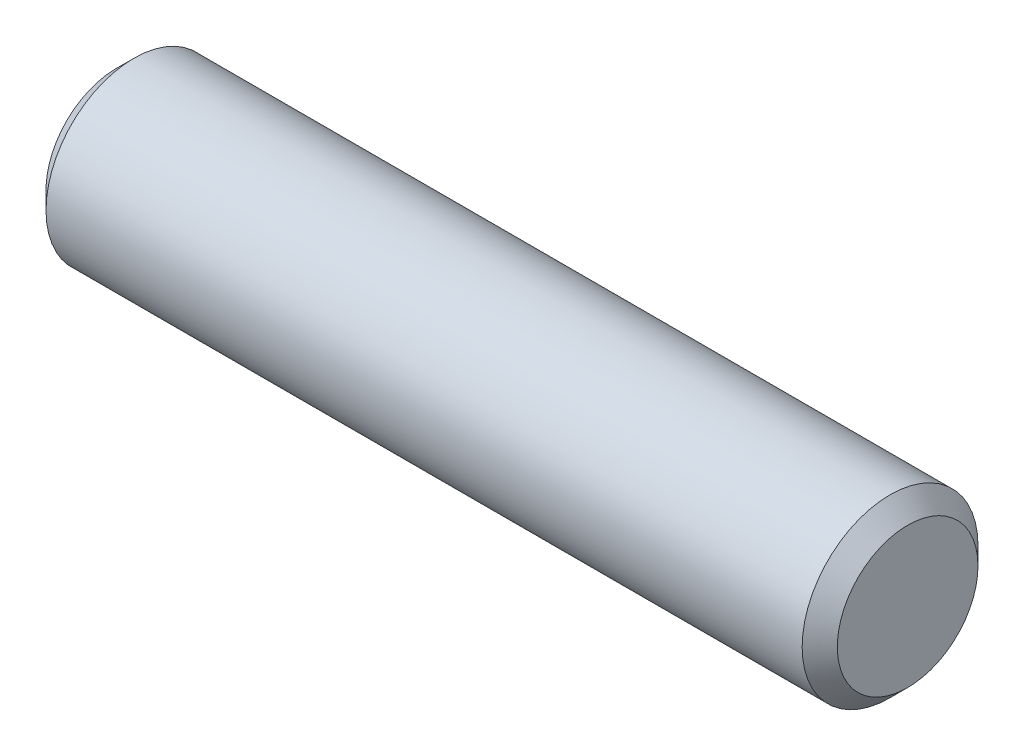
SolidWorks part; units mm, degrees
ref_plane "Front" through (0, 0, 0) normal (0, 0, 1) x (1, 0, 0)
ref_plane "Top" through (0, 0, 0) normal (0, 1, 0) x (1, 0, 0)
ref_plane "Right" through (0, 0, 0) normal (1, 0, 0) x (0, 0, -1)
sketch "Sketch1" plane through (0, 0, 0) normal (0, 0, 1) x (1, 0, 0)
  line L0 (-14.2875, 0) -> (14.2875, 0) construction
  line L1 (14.2875, 3.175) -> (14.2875, -3.175) construction
  line L2 (-14.2875, 3.175) -> (-14.2875, -3.175) construction
  dimension "Length" = 28.575
  dimension "Diameter" = 6.35
sketch "Sketch2" plane through (0, 0, 0) normal (1, 0, 0) x (0, 0, -1)
  circle A0 centre (0, 0) radius 3.175
extrude "Extrude1" add sketch "Sketch2" against normal up to vertex (14.2875 mm away) and the other way up to vertex (14.2875 mm away) up to point (-14.2875, 3.175, 0) other way up to point (14.2875, 3.175, 0)
chamfer "Chamfer1" distance 0.635 angle 45 2 edges at (14.2875, 0, -3.175) (-14.2875, 0, -3.175)
equation "\"D1@Chamfer1\" = \"Diameter@Sketch1\"*.1"
